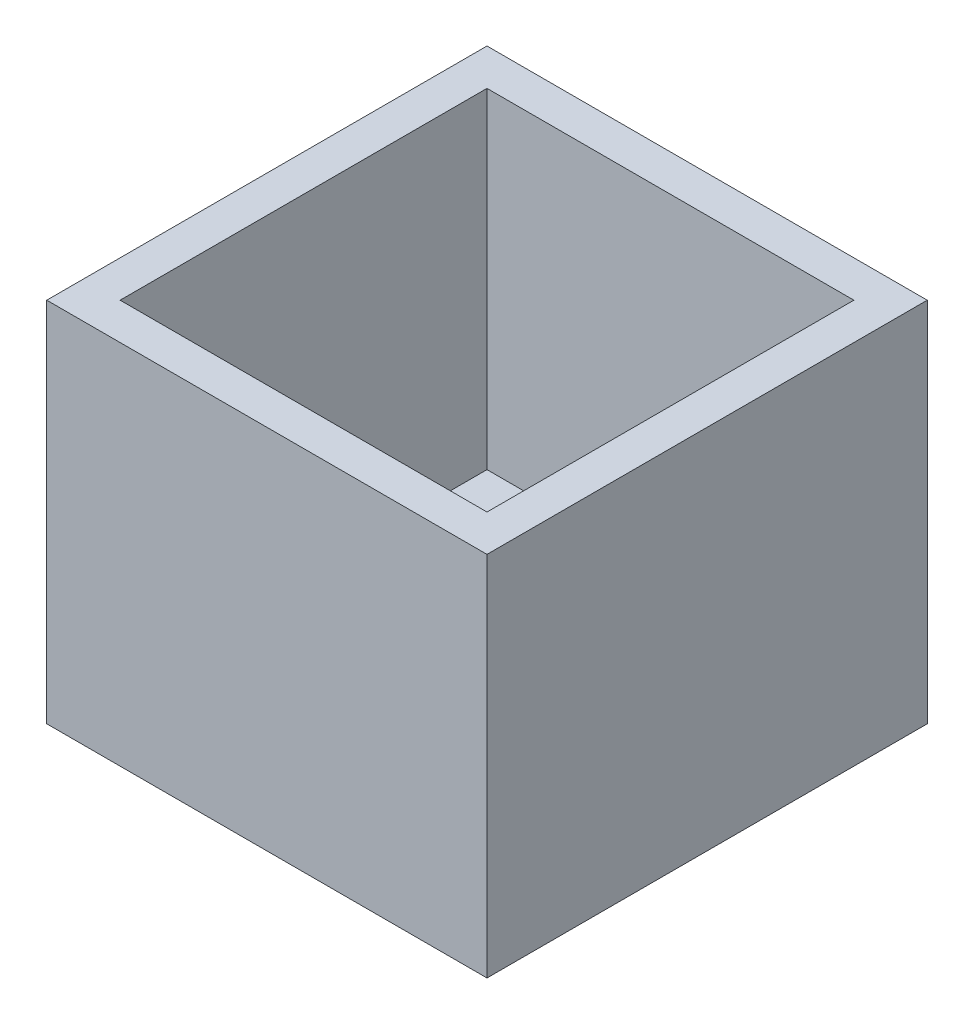
SolidWorks part; units mm, degrees
ref_plane "前视基准面" through (0, 0, 0) normal (0, 0, 1) x (1, 0, 0)
ref_plane "上视基准面" through (0, 0, 0) normal (0, 1, 0) x (1, 0, 0)
ref_plane "右视基准面" through (0, 0, 0) normal (1, 0, 0) x (0, 0, -1)
other "Configuration Table"
sketch "草图1" plane through (0, 0, 0) normal (0, 1, 0) x (1, 0, 0)
  line L1 (-60, 60) -> (60, 60)
  line L2 (-60, 60) -> (-60, -60)
  line L3 (-60, -60) -> (60, -60)
  line L4 (60, 60) -> (60, -60)
  line L5 (-60, 60) -> (60, -60) construction
  line L6 (-60, -60) -> (60, 60) construction
  point P0 (0, 0)
  dimension "D1" = 120
  dimension "D2" = 120
extrude "凸台-拉伸1" add sketch "草图1" along normal blind 100
sketch "草图2" plane through (0, 100, 0) normal (0, 1, 0) x (1, 0, 0)
  line L1 (-50, 50) -> (50, 50)
  line L2 (-50, 50) -> (-50, -50)
  line L3 (-50, -50) -> (50, -50)
  line L4 (50, 50) -> (50, -50)
  line L5 (-50, 50) -> (50, -50) construction
  line L6 (-50, -50) -> (50, 50) construction
  point P0 (0, 0)
  dimension "D1" = 100
  dimension "D2" = 100
extrude "切除-拉伸1" cut sketch "草图2" against normal blind 90
